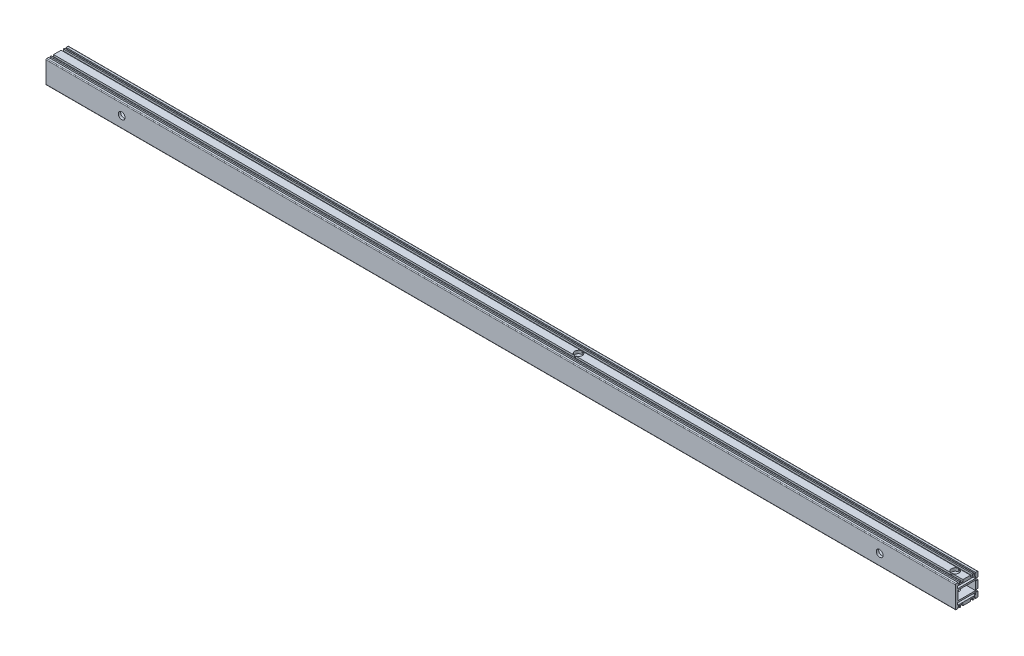
SolidWorks part; units mm, degrees
ref_plane "前视基准面" through (0, 0, 0) normal (0, 0, 1) x (1, 0, 0)
ref_plane "上视基准面" through (0, 0, 0) normal (0, 1, 0) x (1, 0, 0)
ref_plane "右视基准面" through (0, 0, 0) normal (1, 0, 0) x (0, 0, -1)
sketch "草图1" plane through (0, 0, 0) normal (1, 0, 0) x (0, 0, -1)
  line L0 (-15, 15) -> (15, -15) construction
  line L1 (-14, 15) -> (-11.5, 15)
  line L2 (-15, 14) -> (-15, -14)
  line L3 (-14, -15) -> (-11.5, -15)
  line L4 (15, 14) -> (15, 8)
  line L5 (15, 15) -> (-15, -15) construction
  line L6 (-11.5, 15) -> (-11.5, 13.5)
  line L7 (-11.5, 13.5) -> (-11.4, 13.5)
  line L8 (-11, 13.1) -> (-11, 12)
  line L9 (-11, 12) -> (-9.5, 12)
  line L10 (-9.5, 12) -> (-9.5, 15)
  line L11 (-9.5, 15) -> (-8, 15)
  line L12 (-8, 15) -> (-8, 12.5)
  line L13 (-8, 12.5) -> (-5, 12.5)
  line L14 (-5, 12.5) -> (-5, 15)
  line L15 (-5, 15) -> (5, 15)
  line L16 (0, 21.5201) -> (0, -18.309) construction
  line L17 (0, 55) -> (0, -55) construction
  line L18 (5, 12.5) -> (5, 15)
  line L19 (8, 12.5) -> (5, 12.5)
  line L20 (8, 15) -> (8, 12.5)
  line L21 (9.5, 15) -> (8, 15)
  line L22 (9.5, 12) -> (9.5, 15)
  line L23 (11, 12) -> (9.5, 12)
  line L24 (11, 13.1) -> (11, 12)
  line L25 (11.5, 13.5) -> (11.4, 13.5)
  line L26 (11.5, 15) -> (11.5, 13.5)
  line L27 (8, 15) -> (9.5, 15)
  line L28 (11.5, 15) -> (14, 15)
  line L29 (-19.8303, 0) -> (22.13, 0) construction
  line L30 (55, 0) -> (-55, 0) construction
  line L31 (8, -15) -> (9.5, -15)
  line L32 (11.5, -15) -> (11.5, -13.5)
  line L33 (11.5, -13.5) -> (11.4, -13.5)
  line L34 (11, -13.1) -> (11, -12)
  line L35 (11, -12) -> (9.5, -12)
  line L36 (9.5, -12) -> (9.5, -15)
  line L37 (9.5, -15) -> (8, -15)
  line L38 (8, -15) -> (8, -12.5)
  line L39 (8, -12.5) -> (5, -12.5)
  line L40 (5, -12.5) -> (5, -15)
  line L41 (-5, -15) -> (5, -15)
  line L42 (-5, -12.5) -> (-5, -15)
  line L43 (-8, -12.5) -> (-5, -12.5)
  line L44 (-8, -15) -> (-8, -12.5)
  line L45 (-9.5, -15) -> (-8, -15)
  line L46 (-9.5, -12) -> (-9.5, -15)
  line L47 (-11, -12) -> (-9.5, -12)
  line L48 (-11, -13.1) -> (-11, -12)
  line L49 (-11.5, -13.5) -> (-11.4, -13.5)
  line L50 (-11.5, -15) -> (-11.5, -13.5)
  line L51 (-9.5, -15) -> (-8, -15)
  line L52 (-5, -15) -> (5, -15)
  line L53 (8, -15) -> (9.5, -15)
  line L54 (11.5, -15) -> (14, -15)
  line L55 (15, 8) -> (12.5, 8)
  line L56 (12.5, 8) -> (12.5, 5)
  line L57 (12.5, 5) -> (15, 5)
  line L58 (12.5, -5) -> (15, -5)
  line L59 (12.5, -8) -> (12.5, -5)
  line L60 (15, -8) -> (12.5, -8)
  line L61 (15, 5) -> (15, -5)
  line L62 (15, -8) -> (15, -14)
  line L63 (12, -10.5) -> (12, -8.5)
  line L64 (-11.5, 11) -> (11.5, 11)
  line L65 (-12, 10.5) -> (-12, 8.5)
  line L66 (-11.5, 8) -> (11.5, 8)
  line L67 (12, 10.5) -> (12, 8.5)
  line L68 (-11.5, -8) -> (11.5, -8)
  line L69 (-12, -10.5) -> (-12, -8.5)
  line L70 (-11.5, -11) -> (11.5, -11)
  line L72 (-11.75, 6) -> (11.75, 6)
  line L73 (-11.75, 6) -> (-11.75, -6)
  line L74 (-11.75, -6) -> (11.75, -6)
  line L75 (11.75, 6) -> (11.75, -6)
  arc A0 (12, 8.5) -> (11.5, 8) centre (11.5, 8.5) cw
  arc A1 (11.5, 11) -> (12, 10.5) centre (11.5, 10.5) cw
  arc A2 (-11.5, 11) -> (-12, 10.5) centre (-11.5, 10.5) ccw
  arc A3 (-11.5, 8) -> (-12, 8.5) centre (-11.5, 8.5) cw
  arc A4 (-11, -13.1) -> (-11.4, -13.5) centre (-11.4, -13.1) cw
  arc A5 (11.4, -13.5) -> (11, -13.1) centre (11.4, -13.1) cw
  arc A6 (11.4, 13.5) -> (11, 13.1) centre (11.4, 13.1) ccw
  arc A7 (-11, 13.1) -> (-11.4, 13.5) centre (-11.4, 13.1) ccw
  arc A8 (-11.5, -8) -> (-12, -8.5) centre (-11.5, -8.5) ccw
  arc A9 (-11.5, -11) -> (-12, -10.5) centre (-11.5, -10.5) cw
  arc A10 (11.5, -11) -> (12, -10.5) centre (11.5, -10.5) ccw
  arc A11 (12, -8.5) -> (11.5, -8) centre (11.5, -8.5) ccw
  arc A12 (14, 15) -> (15, 14) centre (14, 14) cw
  arc A13 (14, -15) -> (15, -14) centre (14, -14) ccw
  arc A14 (-15, -14) -> (-14, -15) centre (-14, -14) ccw
  arc A15 (-15, 14) -> (-14, 15) centre (-14, 14) cw
  point P69 (12, 11)
  point P72 (-12, 11)
  point P77 (-11, -13.5)
  point P80 (11, -13.5)
  point P83 (11, 13.5)
  point P86 (-11, 13.5)
  point P99 (-12, -11)
  point P100 (12, -11)
  dimension "D17" = 0.5
  dimension "D18" = 0.4
  dimension "D21" = 1
  dimension "D1" = 3.5
  dimension "D2" = 1.5
  dimension "D3" = 0.5
  dimension "D4" = 1.5
  dimension "D5" = 3
  dimension "D6" = 30
  dimension "D7" = 30
  dimension "D8" = 1.5
  dimension "D9" = 2.5
  dimension "D10" = 3
  dimension "D11" = 2.5
  dimension "D12" = 7
  dimension "D13" = 3
  dimension "D14" = 4
  dimension "D15" = 3
  dimension "D16" = 24
  dimension "D19" = 23.5
  dimension "D20" = 12
extrude "凸台-拉伸1" add sketch "草图1" along normal mid plane 1202 contours A15 L2 A14 L3 L50 L49 A4 L48 L47 L46 L45 L44 L43 L42 L41 L40 L39 L38 L31 L36 L35 L34 A5 L33 L32 L54 A13 L62 L60 L59 L58 L61 L57 L56 L55 L4 A12 L28 L26 L25 A6 L24 L23 L22 L21 L20 L19 L18 L15 L14 L13
hole_wizard "M6 螺纹孔1" positions "草图3" profile "草图2" tap size "M6" standard "GB"
sketch "草图3" plane through (0, 0, -15) normal (0, 0, -1) x (-1, 0, 0)
  line L0 (-571, -9) -> (-571, 9) construction
  line L1 (-601, 15) -> (601, 15) construction
  point P0 (-551, 0)
  point P1 (-536, 0)
  point P4 (536, 0)
  point P7 (551, 0)
  dimension "D1" = 20
  dimension "D2" = 15
sketch "草图2" plane through (551, 0, -15) normal (1, 0, 0) x (0, 1, 0)
  line L0 (0, 0) -> (0, 16.5022)
  line L1 (0, 16.5022) -> (2.5, 15)
  line L2 (2.5, 15) -> (2.5, 0)
  line L5 (2.5, 0) -> (0, 0)
  line L10 (0, 16.5022) -> (-2.5, 15) construction
  line L11 (0, -6.35) -> (0, 107.95) construction
  dimension "螺纹孔钻头直径" = 5
  dimension "螺纹孔钻头深度" = 15
  dimension "导头角度" = 118
cosmetic thread "孔螺蚊线1" parameters "D1"=3.25, "D2"=6
cosmetic thread "孔螺蚊线2" parameters "D1"=3.25, "D2"=6
cosmetic thread "孔螺蚊线3" parameters "D1"=3.25, "D2"=6
cosmetic thread "孔螺蚊线4" parameters "D1"=3.25, "D2"=6
hole_wizard "M6 螺纹孔2" positions "草图5" profile "草图4" tap size "M6" standard "GB"
sketch "草图5" plane through (0, -15, 0) normal (0, -1, 0) x (1, 0, 0)
  line L0 (571, 5) -> (571, -5) construction
  line L1 (601, -15) -> (-601, -15) construction
  point P0 (551, 0)
  point P1 (536, 0)
  point P4 (-199, 0)
  point P7 (-214, 0)
  point P10 (-284, 0)
  point P13 (-299, 0)
  point P16 (-536, 0)
  point P19 (-551, 0)
  dimension "D1" = 20
  dimension "D2" = 15
sketch "草图4" plane through (551, -15, 0) normal (1, 0, 0) x (0, 0, -1)
  line L0 (0, 0) -> (0, 16.5022)
  line L1 (0, 16.5022) -> (2.5, 15)
  line L2 (2.5, 15) -> (2.5, 0)
  line L5 (2.5, 0) -> (0, 0)
  line L10 (0, 16.5022) -> (-2.5, 15) construction
  line L11 (0, -6.35) -> (0, 107.95) construction
  dimension "螺纹孔钻头直径" = 5
  dimension "螺纹孔钻头深度" = 15
  dimension "导头角度" = 118
cosmetic thread "孔螺蚊线5" parameters "D1"=9, "D2"=6
cosmetic thread "孔螺蚊线6" parameters "D1"=9, "D2"=6
cosmetic thread "孔螺蚊线7" parameters "D1"=9, "D2"=6
cosmetic thread "孔螺蚊线8" parameters "D1"=9, "D2"=6
cosmetic thread "孔螺蚊线9" parameters "D1"=9, "D2"=6
cosmetic thread "孔螺蚊线10" parameters "D1"=9, "D2"=6
cosmetic thread "孔螺蚊线11" parameters "D1"=9, "D2"=6
cosmetic thread "孔螺蚊线12" parameters "D1"=9, "D2"=6
sketch "草图6" plane through (0, -15, 0) normal (0, -1, 0) x (1, 0, 0)
  circle A0 centre (88, 0) radius 5.05
  circle A1 centre (586, 0) radius 5.05
extrude "切除-拉伸1" cut sketch "草图6" against normal through all
hole_wizard "M4 螺纹孔1" positions "草图9" profile "草图8" tap size "M4" standard "GB"
sketch "草图9" plane through (0, -15, 0) normal (0, -1, 0) x (1, 0, 0)
  line L0 (601, 5) -> (601, -5) construction
  line L1 (601, -15) -> (-601, -15) construction
  point P0 (489, 0)
  point P1 (329, 0)
  point P3 (169, 0)
  point P5 (9, 0)
  point P7 (-151, 0)
  dimension "D1" = 112
  dimension "D2" = 15
  dimension "D3" = 160
  dimension "D4" = 160
  dimension "D5" = 160
  dimension "D6" = 160
sketch "草图8" plane through (489, -15, 0) normal (1, 0, 0) x (0, 0, -1)
  line L0 (0, 0) -> (0, 11.0914)
  line L1 (0, 11.0914) -> (1.65, 10.1)
  line L2 (1.65, 10.1) -> (1.65, 0)
  line L5 (1.65, 0) -> (0, 0)
  line L10 (0, 11.0914) -> (-1.65, 10.1) construction
  line L11 (0, -6.35) -> (0, 107.95) construction
  dimension "螺纹孔钻头直径" = 3.3
  dimension "螺纹孔钻头深度" = 10.1
  dimension "导头角度" = 118
cosmetic thread "孔螺蚊线13" parameters "D1"=8, "D2"=4
cosmetic thread "孔螺蚊线14" parameters "D1"=8, "D2"=4
cosmetic thread "孔螺蚊线15" parameters "D1"=8, "D2"=4
cosmetic thread "孔螺蚊线16" parameters "D1"=8, "D2"=4
cosmetic thread "孔螺蚊线17" parameters "D1"=8, "D2"=4
sketch "草图10" plane through (0, 0, 15) normal (0, 0, 1) x (1, 0, 0)
  line L0 (-601, 14) -> (-601, -14) construction
  line L1 (601, 14) -> (601, -14) construction
  line L2 (585.2911, 15) -> (88.7089, 15) construction
  circle A0 centre (-501, 0) radius 4.5
  circle A1 centre (501, 0) radius 4.5
  dimension "D3" = 15
  dimension "D4" = 9
  dimension "D1" = 100
  dimension "D2" = 100
extrude "切除-拉伸2" cut sketch "草图10" against normal through all
hole_wizard "M4 螺纹孔2" positions "草图12" profile "草图11" tap size "M4" standard "GB"
sketch "草图12" plane through (0, 0, -15) normal (0, 0, -1) x (-1, 0, 0)
  line L0 (-601, 14) -> (-601, -14) construction
  line L2 (-585.2911, 15) -> (-88.7089, 15) construction
  point P1 (-479, 0)
  point P3 (-319, 0)
  point P5 (-159, 0)
  point P7 (1, 0)
  point P9 (161, 0)
  point P11 (321, 0)
  point P13 (481, 0)
  dimension "D1" = 122
  dimension "D2" = 15
  dimension "D3" = 160
  dimension "D4" = 160
  dimension "D5" = 160
  dimension "D6" = 160
  dimension "D7" = 160
  dimension "D8" = 160
sketch "草图11" plane through (479, 0, -15) normal (1, 0, 0) x (0, 1, 0)
  line L0 (0, 0) -> (0, 11.0914)
  line L1 (0, 11.0914) -> (1.65, 10.1)
  line L2 (1.65, 10.1) -> (1.65, 0)
  line L5 (1.65, 0) -> (0, 0)
  line L10 (0, 11.0914) -> (-1.65, 10.1) construction
  line L11 (0, -6.35) -> (0, 107.95) construction
  dimension "螺纹孔钻头直径" = 3.3
  dimension "螺纹孔钻头深度" = 10.1
  dimension "导头角度" = 118
cosmetic thread "孔螺蚊线18" parameters "D1"=3.25, "D2"=4
cosmetic thread "孔螺蚊线19" parameters "D1"=3.25, "D2"=4
cosmetic thread "孔螺蚊线20" parameters "D1"=3.25, "D2"=4
cosmetic thread "孔螺蚊线21" parameters "D1"=3.25, "D2"=4
cosmetic thread "孔螺蚊线22" parameters "D1"=3.25, "D2"=4
cosmetic thread "孔螺蚊线23" parameters "D1"=3.25, "D2"=4
cosmetic thread "孔螺蚊线24" parameters "D1"=3.25, "D2"=4
